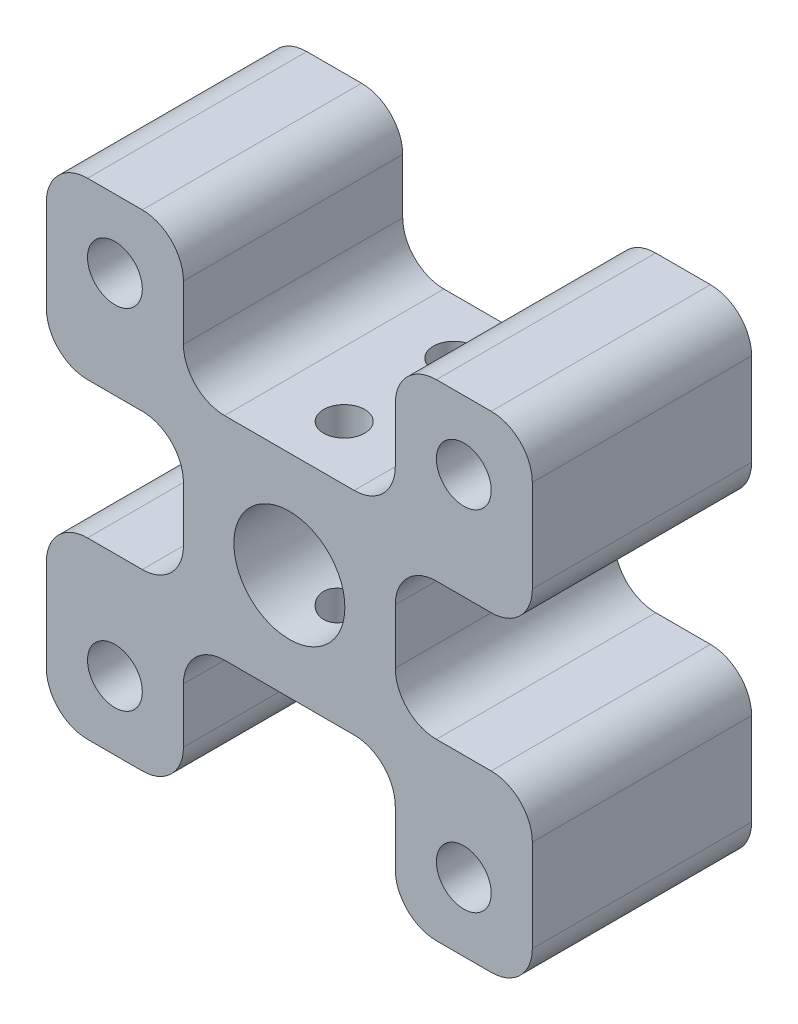
SolidWorks part; units mm, degrees
material "6061 合金"
ref_plane "正面" through (0, 0, 0) normal (0, 0, 1) x (1, 0, 0)
ref_plane "平面" through (0, 0, 0) normal (0, 1, 0) x (1, 0, 0)
ref_plane "右側面" through (0, 0, 0) normal (1, 0, 0) x (0, 0, -1)
sketch "ｽｹｯﾁ1" plane through (0, 0, 0) normal (0, 0, 1) x (1, 0, 0)
  line L0 (-7.7279, 17.7279) -> (-7.7279, 7.7279)
  line L1 (17.7279, -17.7279) -> (7.7279, -17.7279)
  line L2 (17.7279, -17.7279) -> (17.7279, -5)
  line L3 (17.7279, 17.7279) -> (7.7279, 17.7279)
  line L4 (-17.7279, -17.7279) -> (-17.7279, -5)
  line L5 (17.7279, -17.7279) -> (-17.7279, 17.7279) construction
  line L6 (17.7279, 17.7279) -> (-17.7279, -17.7279) construction
  line L7 (12.7279, -12.7279) -> (-12.7279, -12.7279) construction
  line L8 (12.7279, -12.7279) -> (12.7279, 12.7279) construction
  line L9 (12.7279, 12.7279) -> (-12.7279, 12.7279) construction
  line L10 (-12.7279, -12.7279) -> (-12.7279, 12.7279) construction
  line L11 (12.7279, -12.7279) -> (-12.7279, 12.7279) construction
  line L12 (12.7279, 12.7279) -> (-12.7279, -12.7279) construction
  line L17 (5, -5) -> (-5, 5) construction
  line L18 (5, 5) -> (-5, -5) construction
  line L19 (-7.7279, 7.7279) -> (7.7279, 7.7279)
  line L20 (7.7279, 7.7279) -> (7.7279, 17.7279)
  line L21 (-7.7279, -17.7279) -> (-7.7279, -7.7279)
  line L22 (-7.7279, -7.7279) -> (7.7279, -7.7279)
  line L23 (7.7279, -7.7279) -> (7.7279, -17.7279)
  line L24 (-7.7279, 17.7279) -> (-17.7279, 17.7279)
  line L25 (-7.7279, -17.7279) -> (-17.7279, -17.7279)
  line L26 (-17.7279, 5) -> (-7.7279, 5)
  line L27 (-7.7279, 5) -> (-7.7279, -5)
  line L28 (-7.7279, -5) -> (-17.7279, -5)
  line L29 (17.7279, 5) -> (7.7279, 5)
  line L30 (7.7279, 5) -> (7.7279, -5)
  line L31 (7.7279, -5) -> (17.7279, -5)
  line L33 (-17.7279, 5) -> (-17.7279, 17.7279)
  line L34 (17.7279, 5) -> (17.7279, 17.7279)
  circle A0 centre (-12.7279, 12.7279) radius 2
  circle A1 centre (12.7279, 12.7279) radius 2
  circle A2 centre (12.7279, -12.7279) radius 2
  circle A3 centre (-12.7279, -12.7279) radius 2
  circle A4 centre (0, 0) radius 4.05
  point P0 (0, 0)
  point P6 (0, 0)
  point P15 (0, 0)
  dimension "D1" = 4
  dimension "D2" = 18
  dimension "D15" = 8.1
  dimension "D3" = 5
  dimension "D4" = 12.7279
  dimension "D5" = 10
  dimension "D6" = 10
  dimension "D7" = 10
  dimension "D8" = 10
  dimension "D9" = 10
  dimension "D10" = 10
  dimension "D11" = 10
  dimension "D12" = 10
  dimension "D13" = 10
  dimension "D14" = 10
extrude "ﾎﾞｽ - 押し出し1" add sketch "ｽｹｯﾁ1" along normal blind 16
sketch "ｽｹｯﾁ3" plane through (0, 7.7279, 0) normal (0, 1, 0) x (1, 0, 0)
  line L0 (0, 0) -> (0, -16) construction
  line L1 (7.7279, 0) -> (-7.7279, 0) construction
  line L2 (7.7279, -16) -> (-7.7279, -16) construction
  circle A0 centre (0, -4) radius 1.5
  circle A1 centre (0, -12) radius 1.5
  dimension "D1" = 3
  dimension "D2" = 3
  dimension "D3" = 4
  dimension "D4" = 4
fillet "ﾌｨﾚｯﾄ3" radius 3 20 edges at (-7.7279, 5, 8) (-17.7279, 5, 8) (-7.7279, -5, 8) (-17.7279, -5, 8) (-17.7279, -17.7279, 8) (-7.7279, -17.7279, 8) (-7.7279, -7.7279, 8) (7.7279, -7.7279, 8) (17.7279, -17.7279, 8) (7.7279, -17.7279, 8) (17.7279, -5, 8) (7.7279, 5, 8) (7.7279, -5, 8) (17.7279, 5, 8) (17.7279, 17.7279, 8) (7.7279, 17.7279, 8) (7.7279, 7.7279, 8) (-7.7279, 7.7279, 8) (-7.7279, 17.7279, 8) (-17.7279, 17.7279, 8)
extrude "ｶｯﾄ - 押し出し2" cut sketch "ｽｹｯﾁ3" against normal through all
